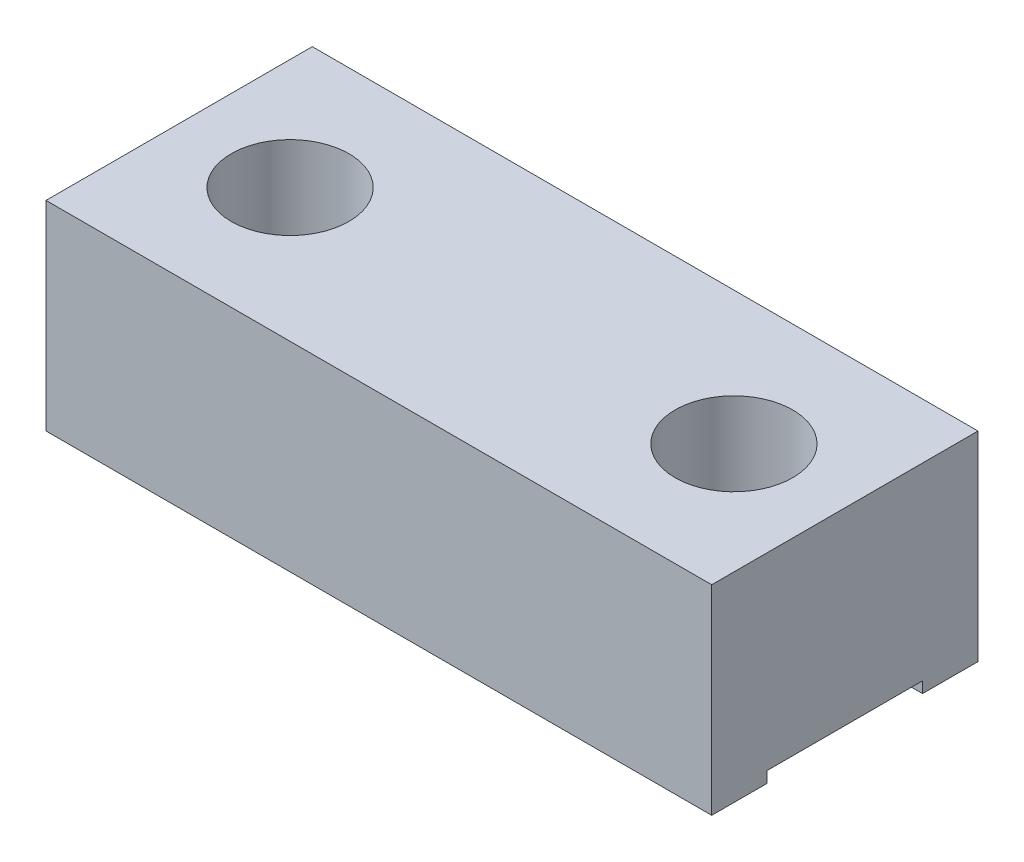
SolidWorks part; units mm, degrees
material "3.3547 (EN-AW 5083)"
ref_plane "Front Plane" through (0, 0, 0) normal (0, 0, 1) x (1, 0, 0)
ref_plane "Top Plane" through (0, 0, 0) normal (0, 1, 0) x (1, 0, 0)
ref_plane "Right Plane" through (0, 0, 0) normal (1, 0, 0) x (0, 0, -1)
sketch3d "3DSketch6"
  line L1 (15, 0.5, -36) -> (-15, 0.5, -36) construction
  line L3 (-15, 0.5, -2) -> (15, 0.5, -2) construction
  line L5 (-15, -0.5, -2) -> (15, -0.5, -2) construction
  line L7 (15, -0.5, -36) -> (-15, -0.5, -36) construction
  line L8 (-10.5, -20.5, 0) -> (10.5, -20.5, 0) construction
  line L9 (12.5, 22.5, 0) -> (-12.5, 22.5, 0) construction
  line L10 (10.5, 20.5, 0) -> (-10.5, 20.5, 0) construction
  line L11 (15, 0.5, -2) -> (15, 0.5, -36)
  line L12 (15, 0.5, -36) -> (-15, 0.5, -36)
  line L13 (-15, 0.5, -36) -> (-15, 0.5, -2)
  line L14 (-15, 0.5, -2) -> (15, 0.5, -2)
  line L15 (-15, -0.5, -36) -> (-15, -0.5, -2)
  line L16 (-15, -0.5, -2) -> (15, -0.5, -2)
  line L17 (15, -0.5, -2) -> (15, -0.5, -36)
  line L18 (15, -0.5, -36) -> (-15, -0.5, -36)
  line L19 (-10.5, -20.5, 0) -> (10.5, -20.5, 0)
  line L20 (12.5, 22.5, 0) -> (-12.5, 22.5, 0)
  line L21 (10.5, 20.5, 0) -> (-10.5, 20.5, 0)
sketch "Sketch3" plane through (0, 0, 0) normal (0, 1, 0) x (1, 0, 0)
  line L0 (12.5, 0) -> (-12.5, 0) construction
  line L1 (12.5, 0) -> (-12.5, 0) construction
  line L2 (10.5, 0) -> (-10.5, 0) construction
  line L3 (10.5, -10) -> (10.5, 0)
  line L4 (10.5, 0) -> (-10.5, 0) construction
  line L5 (10.5, 0) -> (12.5, 0)
  line L6 (-15, 2) -> (15, 2) construction
  line L7 (10.5, -10) -> (-10.5, -10)
  line L8 (-10.5, -10) -> (-10.5, 0)
  line L14 (-10.5, 2) -> (-10.5, 0)
  line L15 (12.5, 2) -> (12.5, 0)
  line L16 (-15, 2) -> (15, 2) construction
  line L17 (12.5, 2) -> (15, 2)
  line L18 (15, 2) -> (15, 14)
  line L19 (15, 14) -> (-15, 14)
  line L20 (-15, 14) -> (-15, 2)
  line L21 (-15, 2) -> (-10.5, 2)
  dimension "D1" = 12
  dimension "D2" = 10
extrude "Boss-Extrude3" add sketch "Sketch3" along normal up to surface (20.5 mm away) and the other way up to surface (20.5 mm away) separate body
sketch "Sketch5" plane through (0, 0, 0) normal (1, 0, 0) x (0, 0, -1)
  line L0 (2, 0.5) -> (4.5, 0.5)
  line L1 (2, 0.5) -> (36, 0.5) construction
  line L2 (4.5, 0.5) -> (4.5, 1)
  line L3 (4.5, 1) -> (11.5, 1)
  line L4 (11.5, 0.5) -> (11.5, 1)
  line L5 (0, 0) -> (14, 0) construction
  line L6 (14, -20.5) -> (14, 20.5) construction
  line L7 (11.5, 0.5) -> (14, 0.5)
  line L8 (14, 0.5) -> (14, -0.5)
  line L9 (2, 0.5) -> (2, -0.5)
  line L10 (11.5, -0.5) -> (14, -0.5)
  line L11 (11.5, -0.5) -> (11.5, -1)
  line L12 (4.5, -1) -> (11.5, -1)
  line L13 (4.5, -0.5) -> (4.5, -1)
  line L14 (2, -0.5) -> (4.5, -0.5)
  line L15 (2, 20.5) -> (2, 9.5)
  line L16 (2, -20.5) -> (14, -20.5) construction
  line L17 (2, -20.5) -> (2, -9.5) construction
  line L18 (2, -9.5) -> (14, -9.5) construction
  line L19 (14, -20.5) -> (14, -9.5) construction
  line L20 (2, 20.5) -> (14, 20.5)
  line L21 (14, 20.5) -> (14, 9.5)
  line L22 (2, 9.5) -> (14, 9.5)
  point P16 (2, 0)
  dimension "D1" = 2.5
  dimension "D2" = 0.5
  dimension "D3" = 9.5
extrude "Cut-Extrude1" cut sketch "Sketch5" against normal through all both and the other way through all
sketch "Sketch6" plane through (-10.5, 0, 0) normal (-1, 0, 0) x (0, 0, 1)
  line L0 (-2, 20.5) -> (-2, -0.5)
  line L1 (-2, -0.5) -> (-2, -20.5) construction
  line L2 (-2, 20.5) -> (0, 20.5) construction
split "Split1" trim tools "Sketch6" bodies to split 118 resulting bodies 119 120
sketch "Sketch11" plane through (0, -1, 0) normal (0, -1, 0) x (-1, 0, 0)
  line L0 (-15, 8) -> (15, 8) construction
  line L1 (-15, 4.5) -> (-15, 11.5) construction
  line L2 (15, 4.5) -> (15, 11.5) construction
  line L4 (0, 0) -> (0, 8) construction
  point P13 (-10, 8)
  point P17 (10, 8)
  dimension "D1" = 5
hole_wizard "M5 Tapped Hole1" positions "Sketch11" profile "Sketch10" tap size "M5" standard "DIN"
sketch "Sketch10" plane through (-10, -1, -8) normal (1, 0, 0) x (0, 0, 1)
  line L0 (0, 0) -> (0, 15.2618)
  line L1 (0, 15.2618) -> (2.1, 14)
  line L2 (2.1, 14) -> (2.1, 0)
  line L5 (2.1, 0) -> (0, 0)
  line L10 (0, 15.2618) -> (-2.1, 14) construction
  line L11 (0, -6.35) -> (0, 107.95) construction
  dimension "Tap Drill Dia." = 4.2
  dimension "Tap Drill Depth" = 14
  dimension "Drill Angle" = 118
cosmetic thread "Hole Thread13" parameters "D1"=10, "D2"=5
cosmetic thread "Hole Thread14" parameters "D1"=10, "D2"=5
sketch "Sketch15" plane through (0, 9.5, 0) normal (0, 1, 0) x (1, 0, 0)
  point P0 (-10, 8)
  point P6 (10, 8)
hole_wizard "M5 Clearance Hole1" positions "Sketch15" profile "Sketch13" hole size "M5" standard "DIN" end condition up to next
sketch "Sketch13" plane through (-10, 9.5, -8) normal (1, 0, 0) x (0, 0, 1)
  line L0 (0, 0) -> (0, 8.5)
  line L1 (0, 8.5) -> (2.65, 8.5)
  line L2 (2.65, 8.5) -> (2.65, 0)
  line L5 (2.65, 0) -> (0, 0)
  line L11 (0, -6.35) -> (0, 107.95) construction
  dimension "Thru Hole Dia." = 5.3
  dimension "Thru Hole Depth" = 8.5
other "Move Face1" [suppressed] parameters "D1"=0.375
other "Move Face2" [suppressed] parameters "D1"=0.275
hole_wizard "M4 Tapped Hole1" positions "3DSketch7" profile "Sketch4" tap size "M4" standard "DIN"
sketch3d "3DSketch7"
  line L0 (10.5, 20.5, 5) -> (10.5, 12.5, 5) construction
  line L1 (10.5, 20.5, 0) -> (10.5, 20.5, 10) construction
  point P0 (10.5, 12.5, 5)
  point P2 (10.5, -12.5, 5)
  point P14 (-10.5, 12.5, 5)
  point P16 (-10.5, -12.5, 5)
  dimension "D1" = 8
cosmetic thread "Hole Thread7" parameters "D2"=4
cosmetic thread "Hole Thread8" parameters "D2"=4
cosmetic thread "Hole Thread9" parameters "D2"=4
cosmetic thread "Hole Thread10" parameters "D2"=4
sketch "Sketch4" plane through (10.5, 12.5, 5) normal (0, 1, 0) x (0, 0, -1)
  line L0 (0, 0) -> (0, 25.5)
  line L1 (0, 25.5) -> (1.65, 25.5)
  line L2 (1.65, 25.5) -> (1.65, 0)
  line L5 (1.65, 0) -> (0, 0)
  line L11 (0, -6.35) -> (0, 107.95) construction
  dimension "Thru Tap Drill Dia." = 3.3
  dimension "Thru Tap Drill Depth" = 25.5
chamfer "Chamfer1" distance 2 angle 45 4 edges at (10.5, -20.5, 5) (-10.5, -20.5, 4) (10.5, 20.5, 5) (-10.5, 20.5, 4)
chamfer "Chamfer2" distance 1 angle 60 8 edges at (-9.5, -19.5, 10) (-10.5, 0, 10) (-9.5, 19.5, 10) (0, 20.5, 10) (9.5, 19.5, 10) (10.5, 0, 10) (9.5, -19.5, 10) (0, -20.5, 10)
fillet "Fillet1" radius 0.2 1 edges at (1, -0.5, -2)
mirror "Mirror1" [suppressed] about plane through (0, 0, 0) normal (1, 0, 0)
cosmetic thread "Hole Thread15" [suppressed] parameters "D1"=10, "D2"=5
cosmetic thread "Hole Thread16" [suppressed] parameters "D2"=4
cosmetic thread "Hole Thread17" [suppressed] parameters "D2"=4
cosmetic thread "Hole Thread18" [suppressed] parameters "D2"=4
cosmetic thread "Hole Thread19" [suppressed] parameters "D2"=4
cosmetic thread "Hole Thread20" [suppressed] parameters "D1"=10, "D2"=5
delete or keep bodies "Body-Delete/Keep 1" [suppressed] type delete bodies bodies 117 122
delete or keep bodies "Body-Delete/Keep 2" [suppressed] type delete bodies bodies 122
delete or keep bodies "Body-Delete/Keep 3" [suppressed] type delete bodies bodies 123
delete or keep bodies "Body-Delete/Keep 4" type delete bodies bodies 117
